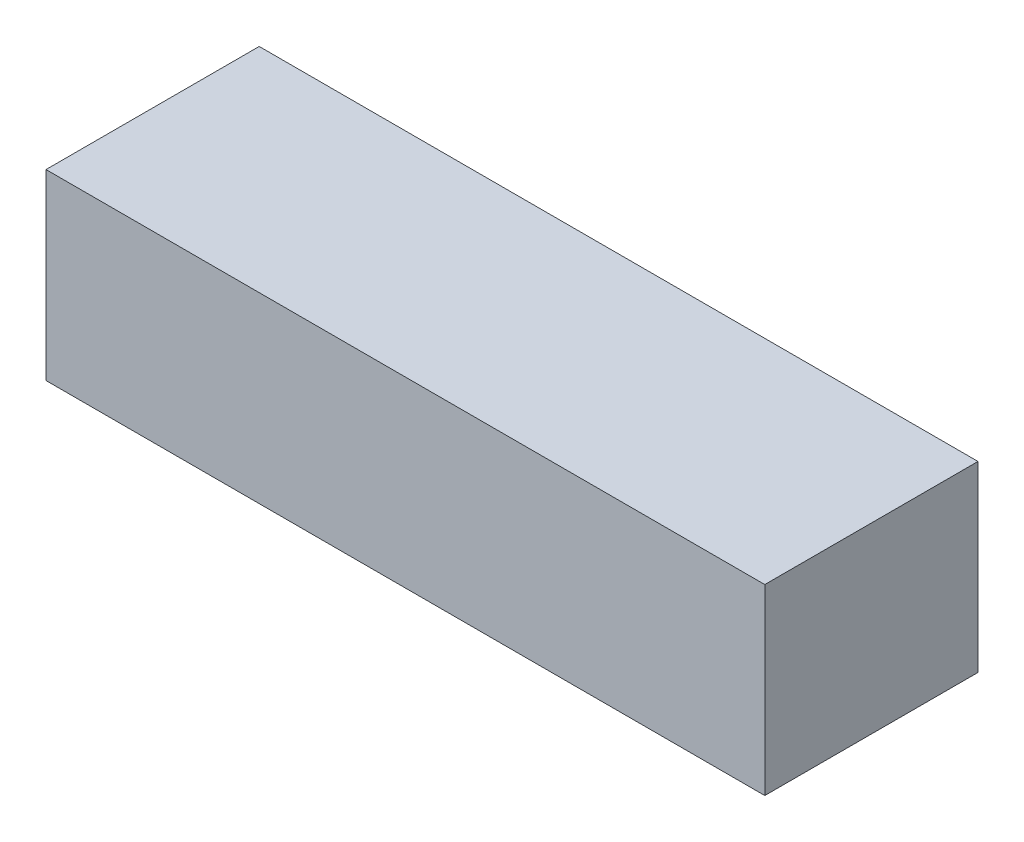
SolidWorks part; units mm, degrees
ref_plane "前视基准面" through (0, 0, 0) normal (0, 0, 1) x (1, 0, 0)
ref_plane "上视基准面" through (0, 0, 0) normal (0, 1, 0) x (1, 0, 0)
ref_plane "右视基准面" through (0, 0, 0) normal (1, 0, 0) x (0, 0, -1)
other "Configuration Table"
sketch "草图1" plane through (0, 0, 0) normal (0, 0, 1) x (1, 0, 0)
  line L1 (0, 0) -> (118, 0)
  line L2 (0, 0) -> (0, -30)
  line L3 (0, -30) -> (118, -30)
  line L4 (118, 0) -> (118, -30)
  dimension "D1" = 118
  dimension "D2" = 30
extrude "凸台-拉伸1" add sketch "草图1" along normal blind 35
